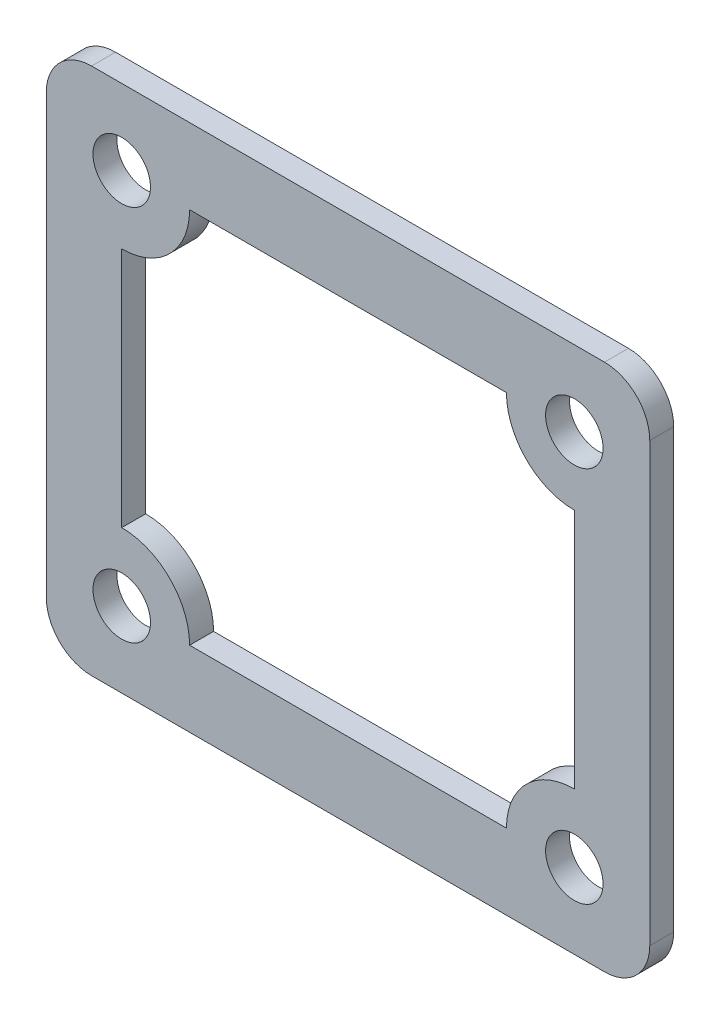
SolidWorks part; units mm, degrees
material "BUTYL"
ref_plane "Front Plane" through (0, 0, 0) normal (0, 0, 1) x (1, 0, 0)
ref_plane "Top Plane" through (0, 0, 0) normal (0, 1, 0) x (1, 0, 0)
ref_plane "Right Plane" through (0, 0, 0) normal (1, 0, 0) x (0, 0, -1)
sketch "Sketch1" plane through (0, 0, 0) normal (0, 0, 1) x (1, 0, 0)
  line L1 (-20, 0) -> (20, 0) construction
  line L2 (-20, 17.5) -> (20, 17.5)
  line L3 (-20, 17.5) -> (-20, -17.5)
  line L4 (-20, -17.5) -> (20, -17.5)
  line L5 (20, 17.5) -> (20, -17.5)
  line L6 (-20, 17.5) -> (20, -17.5) construction
  line L7 (-20, -17.5) -> (20, 17.5) construction
  line L8 (0, 17.5) -> (0, -17.5) construction
  line L16 (-15, 8) -> (-15, -8)
  line L17 (10.5, -12.5) -> (-10.5, -12.5)
  line L20 (15, 8) -> (15, -8)
  line L26 (10.5, 12.5) -> (-10.5, 12.5)
  arc A5 (-10.5, -12.5) -> (-15, -8) centre (-15, -12.5) ccw
  arc A6 (10.5, -12.5) -> (15, -8) centre (15, -12.5) cw
  arc A9 (10.5, 12.5) -> (15, 8) centre (15, 12.5) ccw
  arc A10 (-10.5, 12.5) -> (-15, 8) centre (-15, 12.5) cw
  circle A12 centre (-15, -12.5) radius 1.905
  circle A13 centre (15, -12.5) radius 1.905
  circle A14 centre (15, 12.5) radius 1.905
  circle A15 centre (-15, 12.5) radius 1.905
  point P0 (0, 15.5)
  point P7 (-15, 0)
  point P24 (0, -12.5)
  point P26 (0, -15.5)
  point P39 (18, 0)
  point P40 (15, 0)
  point P42 (-18, 0)
  point P43 (0, 12.5)
  dimension "D11" = 4.5
  dimension "D1" = 40
  dimension "D2" = 35
  dimension "D3" = 5
  dimension "D4" = 5
  dimension "D6" = 5
extrude "Boss-Extrude1" add sketch "Sketch1" along normal blind 1.5875
fillet "Fillet1" radius 3 4 edges at (20, 17.5, 0.7937) (-20, 17.5, 0.7937) (-20, -17.5, 0.7937) (20, -17.5, 0.7937)
